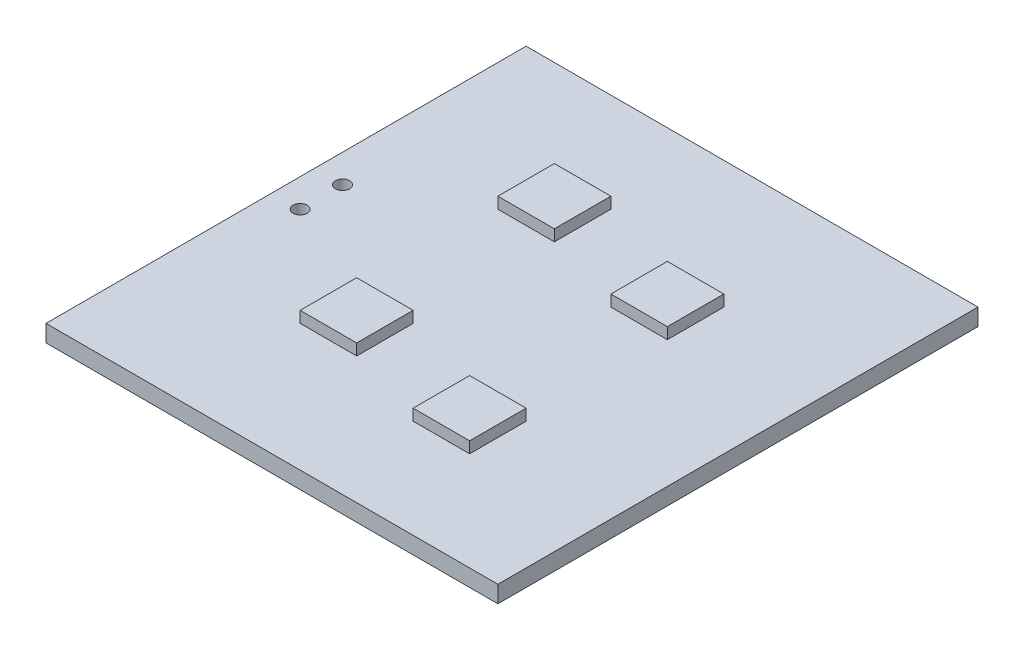
SolidWorks part; units mm, degrees
material "PBT General Purpose"
ref_plane "Front Plane" through (0, 0, 0) normal (0, 0, 1) x (1, 0, 0)
ref_plane "Top Plane" through (0, 0, 0) normal (0, 1, 0) x (1, 0, 0)
ref_plane "Right Plane" through (0, 0, 0) normal (1, 0, 0) x (0, 0, -1)
sketch "Sketch2" plane through (0, 0, 0) normal (0, 1, 0) x (1, 0, 0)
  line L1 (0, 0) -> (40.64, 0)
  line L2 (0, 0) -> (0, 43.18)
  line L3 (0, 43.18) -> (40.64, 43.18)
  line L4 (40.64, 0) -> (40.64, 43.18)
  dimension "D1" = 43.18
  dimension "D2" = 40.64
extrude "Boss-Extrude1" add sketch "Sketch2" along normal blind 1.524
sketch "Sketch3" plane through (0, 1.524, 0) normal (0, 1, 0) x (1, 0, 0)
  line L0 (2.54, 24.13) -> (2.54, 20.32) construction
  line L1 (0, 43.18) -> (0, 0) construction
  line L2 (40.64, 43.18) -> (0, 43.18) construction
  circle A0 centre (2.54, 24.13) radius 0.635
  circle A1 centre (2.54, 20.32) radius 0.635
  dimension "D1" = 1.27
  dimension "D2" = 1.27
  dimension "D5" = 19.05
  dimension "D3" = 3.81
  dimension "D4" = 2.54
extrude "Cut-Extrude1" cut sketch "Sketch3" against normal through all
sketch "Sketch4" plane through (0, 1.524, 0) normal (0, 1, 0) x (1, 0, 0)
  line L0 (40.64, 43.18) -> (0, 43.18) construction
  line L1 (11.43, 34.29) -> (16.51, 34.29)
  line L2 (11.43, 34.29) -> (11.43, 29.21)
  line L3 (11.43, 29.21) -> (16.51, 29.21)
  line L4 (16.51, 34.29) -> (16.51, 29.21)
  line L5 (24.13, 31.75) -> (29.21, 31.75)
  line L6 (24.13, 31.75) -> (24.13, 26.67)
  line L7 (24.13, 26.67) -> (29.21, 26.67)
  line L8 (29.21, 31.75) -> (29.21, 26.67)
  line L9 (11.43, 16.51) -> (16.51, 16.51)
  line L10 (11.43, 16.51) -> (11.43, 11.43)
  line L11 (11.43, 11.43) -> (16.51, 11.43)
  line L12 (16.51, 16.51) -> (16.51, 11.43)
  line L13 (24.13, 13.97) -> (29.21, 13.97)
  line L14 (24.13, 13.97) -> (24.13, 8.89)
  line L15 (24.13, 8.89) -> (29.21, 8.89)
  line L16 (29.21, 13.97) -> (29.21, 8.89)
  line L17 (0, 43.18) -> (0, 0) construction
  line L18 (0, 0) -> (40.64, 0) construction
  line L19 (40.64, 0) -> (40.64, 43.18) construction
  dimension "D1" = 5.08
  dimension "D2" = 8.89
  dimension "D3" = 11.43
  dimension "D4" = 11.43
  dimension "D5" = 11.43
  dimension "D6" = 11.43
  dimension "D7" = 11.43
  dimension "D8" = 8.89
  dimension "D9" = 11.43
extrude "Boss-Extrude2" add sketch "Sketch4" along normal blind 1.016
